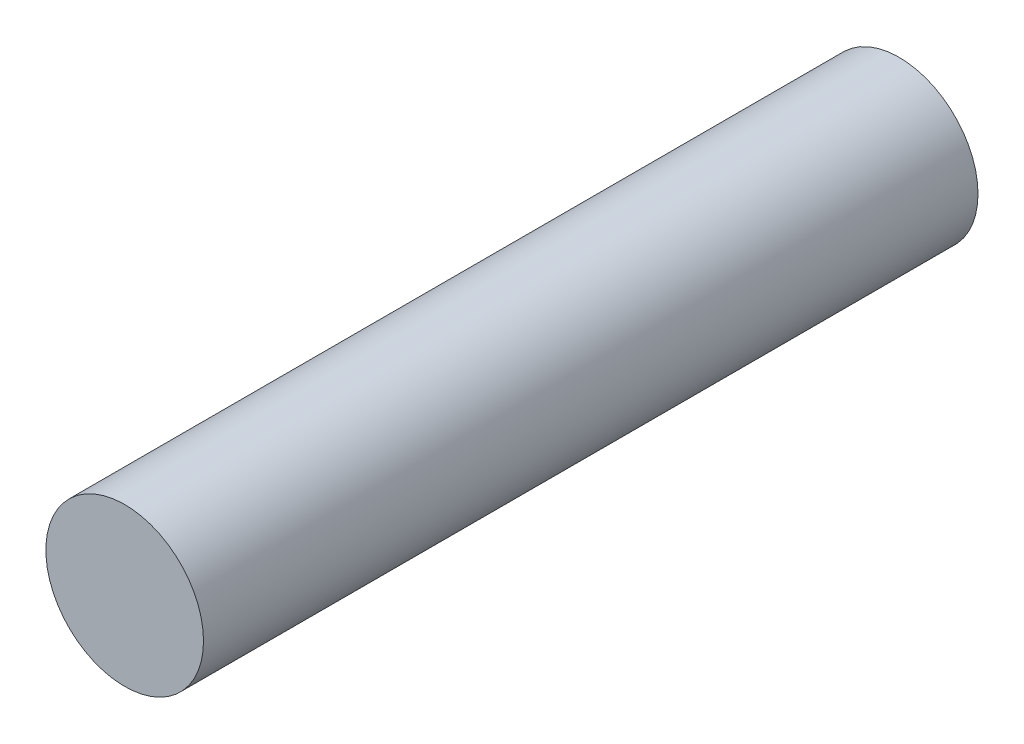
SolidWorks part; units mm, degrees
ref_plane "Front Plane" through (0, 0, 0) normal (0, 0, 1) x (1, 0, 0)
ref_plane "Top Plane" through (0, 0, 0) normal (0, 1, 0) x (1, 0, 0)
ref_plane "Right Plane" through (0, 0, 0) normal (1, 0, 0) x (0, 0, -1)
sketch "Sketch1" plane through (0, 0, 0) normal (0, 0, 1) x (1, 0, 0)
  circle A0 centre (0, 0) radius 2
extrude "Boss-Extrude1" add sketch "Sketch1" along normal blind 19.65
